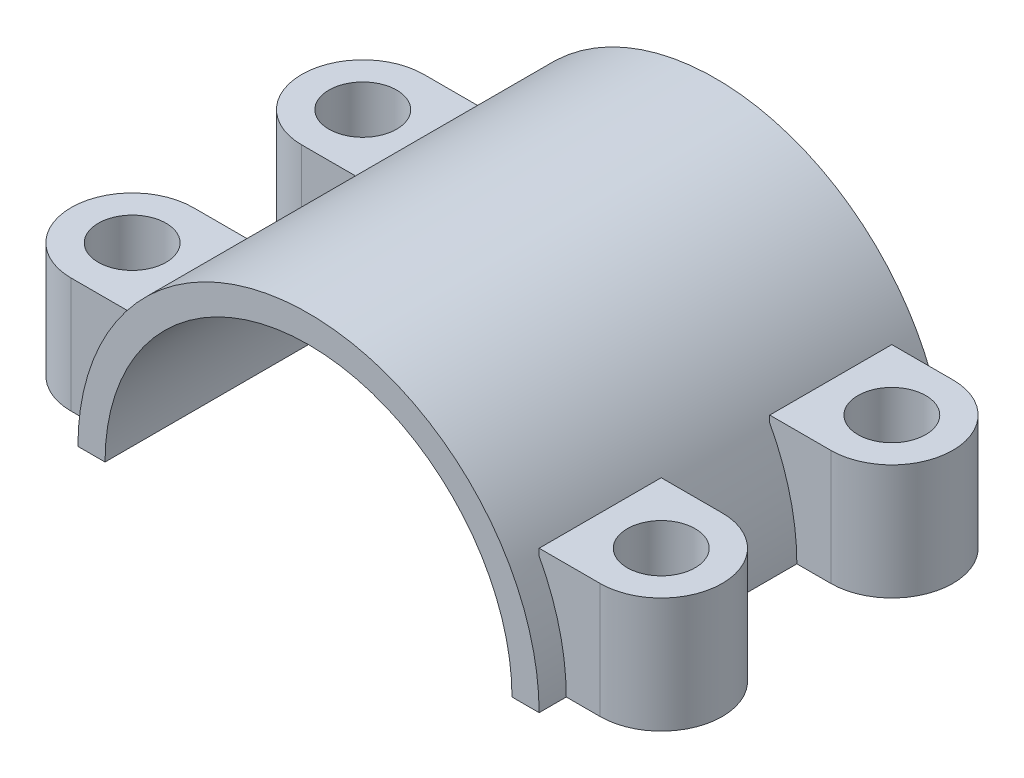
SolidWorks part; units mm, degrees
material "Custom Plastic"
ref_plane "X-Y Datum" through (0, 0, 0) normal (0, 0, 1) x (1, 0, 0)
ref_plane "X-Z Datum" through (0, 0, 0) normal (0, 1, 0) x (1, 0, 0)
ref_plane "Y-Z Datum" through (0, 0, 0) normal (1, 0, 0) x (0, 0, -1)
sketch "Sketch1" plane through (0, 0, 0) normal (0, 0, 1) x (1, 0, 0)
  line L0 (-21.59, 0) -> (-19.05, 0)
  line L1 (19.05, 0) -> (21.59, 0)
  arc A0 (19.05, 0) -> (-19.05, 0) centre (0, 0) ccw
  arc A1 (21.59, 0) -> (-21.59, 0) centre (0, 0) ccw
  dimension "D1" = 2.54
  dimension "D2" = 19.05
extrude "Boss-Extrude2" add sketch "Sketch1" along normal blind 38.1
sketch "Sketch8" plane through (0, 0, 0) normal (0, 1, 0) x (1, 0, 0)
  line L0 (-21.59, -38.1) -> (-21.59, -29.845)
  line L1 (-21.59, -38.1) -> (-21.59, 0) construction
  line L2 (-21.59, 0) -> (-21.59, -8.255)
  line L3 (-11.8745, 0) -> (11.8745, 0) construction
  line L4 (-21.59, -8.255) -> (-24.765, -8.255)
  line L5 (-21.59, -29.845) -> (-24.765, -29.845)
  circle A0 centre (-24.765, -8.255) radius 5.715
  circle A1 centre (-24.765, -29.845) radius 5.715
extrude "Boss-Extrude3" add sketch "Sketch8" along normal blind 10.795 contours A1 | A0
sketch "Sketch9" plane through (0, 0, 0) normal (0, 1, 0) x (1, 0, 0)
  line L0 (-24.765, -24.13) -> (-19.05, -24.13)
  line L1 (-19.05, -24.13) -> (-19.05, -35.56)
  line L2 (-19.05, -35.56) -> (-24.765, -35.56)
  line L3 (-24.765, -35.56) -> (-24.765, -24.13)
  line L4 (-24.765, -13.97) -> (-19.05, -13.97)
  line L5 (-19.05, -13.97) -> (-19.05, -2.54)
  line L6 (-19.05, -2.54) -> (-24.765, -2.54)
  line L7 (-24.765, -2.54) -> (-24.765, -13.97)
  circle A0 centre (-24.765, -29.845) radius 5.715 construction
  circle A1 centre (-24.765, -8.255) radius 5.715 construction
extrude "Boss-Extrude4" add sketch "Sketch9" along normal blind 10.795
sketch "Sketch10" plane through (0, 10.795, 0) normal (0, 1, 0) x (1, 0, 0)
  circle A0 centre (-24.765, -29.845) radius 3.175
  circle A1 centre (-24.765, -8.255) radius 3.175
extrude "Cut-Extrude1" cut sketch "Sketch10" against normal blind 10.795 contours A0 | A1
mirror "Mirror1" about plane through (0, 0, 0) normal (1, 0, 0) of "Cut-Extrude1", "Boss-Extrude4", "Boss-Extrude3"
